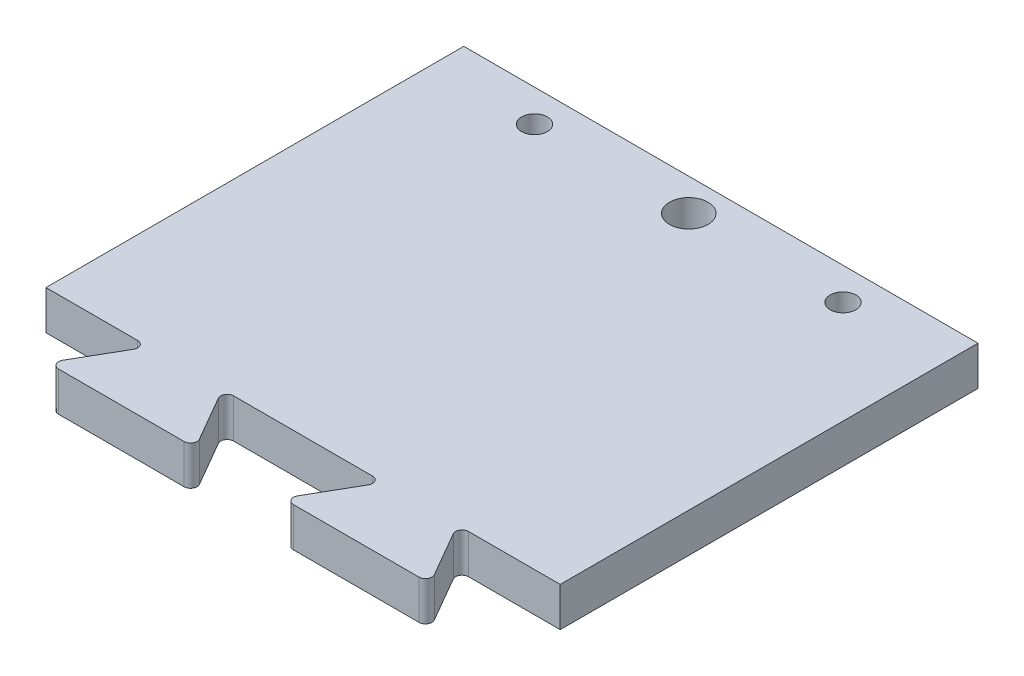
SolidWorks part; units mm, degrees
ref_plane "Front Plane" through (0, 0, 0) normal (0, 0, 1) x (1, 0, 0)
ref_plane "Top Plane" through (0, 0, 0) normal (0, 1, 0) x (1, 0, 0)
ref_plane "Right Plane" through (0, 0, 0) normal (1, 0, 0) x (0, 0, -1)
sketch "Sketch1" plane through (0, 0, 0) normal (0, 1, 0) x (1, 0, 0)
  line L0 (0, 0) -> (0, 32.5)
  line L1 (0, 32.5) -> (40, 32.5)
  line L2 (40, 32.5) -> (40, 0)
  line L3 (40, 0) -> (32, 0)
  line L4 (32, 0) -> (34.8868, -5)
  line L5 (34.8868, -5) -> (23.3868, -5)
  line L6 (23.3868, -5) -> (26.2735, 0)
  line L7 (26.2735, 0) -> (13.7265, 0)
  line L8 (13.7265, 0) -> (16.6132, -5)
  line L9 (16.6132, -5) -> (5.1132, -5)
  line L10 (5.1132, -5) -> (8, 0)
  line L11 (8, 0) -> (0, 0)
  dimension "D1" = 32.5
  dimension "D2" = 40
  dimension "D3" = 11.5
  dimension "D4" = 11.5
  dimension "D5" = 60
  dimension "D6" = 60
  dimension "D7" = 8
  dimension "D8" = 8
  dimension "D9" = 5
  dimension "D10" = 5
extrude "Boss-Extrude1" add sketch "Sketch1" along normal blind 3.05
sketch "Sketch2" plane through (0, 3.05, 0) normal (0, 1, 0) x (1, 0, 0)
  line L0 (0, 32.5) -> (8, 32.5) construction
  line L1 (40, 32.5) -> (0, 32.5) construction
  line L2 (8, 32.5) -> (8, 30) construction
  line L3 (8, 30) -> (32, 30) construction
  line L4 (32, 30) -> (32, 32.5) construction
  line L5 (32, 32.5) -> (40, 32.5) construction
  circle A0 centre (8, 30) radius 1
  circle A1 centre (32, 30) radius 1
  circle A2 centre (20, 30) radius 1.5
  dimension "D4" = 2
  dimension "D5" = 2
  dimension "D6" = 3
  dimension "D1" = 8
  dimension "D2" = 2.5
  dimension "D3" = 8
extrude "Cut-Extrude1" cut sketch "Sketch2" against normal blind 10
fillet "Fillet1" radius 0.5 8 edges at (32, 1.525, 0) (34.8868, 1.525, 5) (23.3868, 1.525, 5) (26.2735, 1.525, 0) (13.7265, 1.525, 0) (16.6132, 1.525, 5) (5.1132, 1.525, 5) (8, 1.525, 0)
